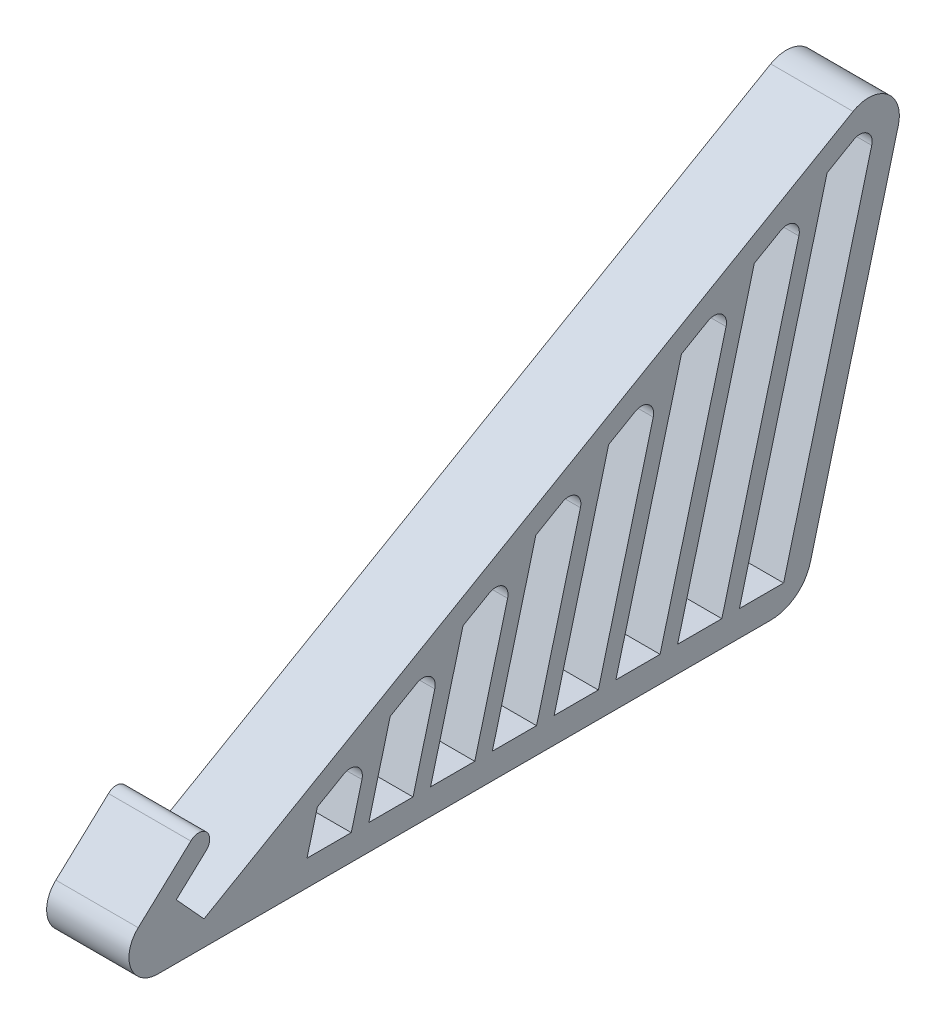
SolidWorks part; units mm, degrees
ref_plane "Front Plane" through (0, 0, 0) normal (0, 0, 1) x (1, 0, 0)
ref_plane "Top Plane" through (0, 0, 0) normal (0, 1, 0) x (1, 0, 0)
ref_plane "Right Plane" through (0, 0, 0) normal (1, 0, 0) x (0, 0, -1)
sketch "Sketch1" plane through (0, 0, 0) normal (1, 0, 0) x (0, 0, -1)
  line L7 (-99.3154, -30.3425) -> (58.3099, 60.6624)
  line L13 (-106.0518, -22.9519) -> (-99.3154, -30.3425)
  line L17 (-110.5364, -36.3425) -> (38.2968, -36.3425)
  line L31 (52.0175, 50.9141) -> (30.7099, -30.0881)
  line L32 (62.8473, 51.2643) -> (41.4476, -30.0881)
  line L43 (-115.292, -24.206) -> (-102.5176, -12.379)
  line L45 (-98.7138, -16.1582) -> (-106.0518, -22.9519)
  line L59 (15.7099, -30.0881) -> (26.4476, -30.0881)
  line L70 (0.7099, -30.0881) -> (11.4476, -30.0881)
  line L73 (52.0175, 50.9141) -> (58.446, 54.6256)
  line L84 (30.7099, -30.0881) -> (41.4476, -30.0881)
  line L117 (-14.2901, -30.0881) -> (-3.5524, -30.0881)
  line L121 (-29.2901, -30.0881) -> (-18.5524, -30.0881)
  line L125 (-44.2901, -30.0881) -> (-33.5524, -30.0881)
  line L129 (-59.2901, -30.0881) -> (-48.5524, -30.0881)
  line L137 (-74.2901, -30.0881) -> (-63.5524, -30.0881)
  line L140 (40.76, 44.4146) -> (34.3315, 40.7031)
  line L141 (-71.7845, -20.563) -> (-74.2901, -30.0881)
  line L142 (-60.9547, -20.2128) -> (-63.5524, -30.0881)
  line L143 (-54.0985, -10.352) -> (-59.2901, -30.0881)
  line L144 (-43.2687, -10.0018) -> (-48.5524, -30.0881)
  line L145 (-36.4125, -0.141) -> (-44.2901, -30.0881)
  line L146 (-25.5827, 0.2092) -> (-33.5524, -30.0881)
  line L147 (-18.7265, 10.07) -> (-29.2901, -30.0881)
  line L148 (45.1613, 41.0533) -> (26.4476, -30.0881)
  line L149 (34.3315, 40.7031) -> (15.7099, -30.0881)
  line L150 (27.4753, 30.8423) -> (11.4476, -30.0881)
  line L151 (16.6455, 30.492) -> (0.7099, -30.0881)
  line L152 (9.7893, 20.6313) -> (-3.5524, -30.0881)
  line L153 (-1.0405, 20.281) -> (-14.2901, -30.0881)
  line L154 (-7.8967, 10.4203) -> (-18.5524, -30.0881)
  line L155 (-52.495, 52.7674) -> (-69.1482, -10.5409) [skipped]
  line L156 (-39.8346, 60.0769) -> (-56.4878, -3.2314) [skipped]
  line L157 (-37.495, 52.7674) -> (-51.4622, -0.3299) [skipped]
  line L158 (-24.8346, 60.0769) -> (-38.8018, 6.9797) [skipped]
  line L159 (-22.495, 52.7674) -> (-33.7762, 9.8812) [skipped]
  line L160 (-9.8346, 60.0769) -> (-21.1158, 17.1907) [skipped]
  line L161 (-7.495, 52.7674) -> (-16.0902, 20.0922) [skipped]
  line L162 (5.1654, 60.0769) -> (-3.4298, 27.4017) [skipped]
  line L163 (7.505, 52.7674) -> (1.5958, 30.3032) [skipped]
  line L164 (20.1654, 60.0769) -> (14.2562, 37.6127) [skipped]
  line L165 (22.505, 52.7674) -> (19.2818, 40.5142) [skipped]
  line L166 (35.1654, 60.0769) -> (31.9422, 47.8237) [skipped]
  line L167 (37.0175, 50.9141) -> (49.6779, 58.2236) [skipped]
  line L168 (22.0175, 50.9141) -> (34.6779, 58.2236) [skipped]
  line L169 (7.0175, 50.9141) -> (19.6779, 58.2236) [skipped]
  line L170 (-7.9825, 50.9141) -> (4.6779, 58.2236) [skipped]
  line L171 (-22.9825, 50.9141) -> (-10.3221, 58.2236) [skipped]
  line L172 (-37.9825, 50.9141) -> (-25.3221, 58.2236) [skipped]
  line L173 (-52.9825, 50.9141) -> (-40.3221, 58.2236) [skipped]
  line L174 (37.505, 52.7674) -> (36.9678, 50.7252) [skipped]
  line L175 (50.1654, 60.0769) -> (49.6282, 58.0347) [skipped]
  line L176 (-65.356, -16.8515) -> (-71.7845, -20.563)
  line L177 (-47.67, -6.6405) -> (-54.0985, -10.352)
  line L178 (-29.984, 3.5705) -> (-36.4125, -0.141)
  line L179 (-12.298, 13.7815) -> (-18.7265, 10.07)
  line L180 (5.388, 23.9925) -> (-1.0405, 20.281)
  line L181 (23.074, 34.2035) -> (16.6455, 30.492)
  line L182 (69.3131, 52.2593) -> (47.9678, -28.8865)
  arc A0 (58.3099, 60.6624) -> (69.3131, 52.2593) centre (62.0599, 54.1673) cw
  arc A1 (58.446, 54.6256) -> (62.8473, 51.2643) centre (59.946, 52.0275) cw
  arc A2 (40.76, 44.4146) -> (45.1613, 41.0533) centre (42.26, 41.8165) cw
  arc A3 (23.074, 34.2035) -> (27.4753, 30.8423) centre (24.574, 31.6055) cw
  arc A4 (5.388, 23.9925) -> (9.7893, 20.6313) centre (6.888, 21.3945) cw
  arc A5 (-12.298, 13.7815) -> (-7.8967, 10.4203) centre (-10.798, 11.1834) cw
  arc A6 (-29.984, 3.5705) -> (-25.5827, 0.2092) centre (-28.484, 0.9724) cw
  arc A7 (-47.67, -6.6405) -> (-43.2687, -10.0018) centre (-46.17, -9.2386) cw
  arc A8 (-65.356, -16.8515) -> (-60.9547, -20.2128) centre (-63.856, -19.4496) cw
  arc A9 (-115.292, -24.206) -> (-110.5364, -36.3425) centre (-110.5364, -29.3425) ccw
  arc A10 (47.9678, -28.8865) -> (38.2968, -36.3425) centre (38.2968, -26.3425) cw
  arc A11 (-102.5176, -12.379) -> (-98.7138, -16.1582) centre (-100.6157, -14.2686) cw
  point P7 (73.8897, 69.6575)
  point P29 (29.3059, 37.8016)
  point P36 (11.6199, 27.5905)
  point P46 (-6.0661, 17.3795)
  point P56 (-23.7521, 7.1685)
  point P60 (-41.4381, -3.0425)
  point P64 (-59.1241, -13.2535)
  dimension "D4" = 7
  dimension "D5" = 200
  dimension "D3" = 3
  dimension "D9" = 3
  dimension "D6" = 10
  dimension "D1" = 8
  dimension "D2" = 30
  dimension "D7" = 6
  dimension "D8" = 10
  dimension "D10" = 10
extrude "Boss-Extrude1" add sketch "Sketch1" along normal mid plane 20
